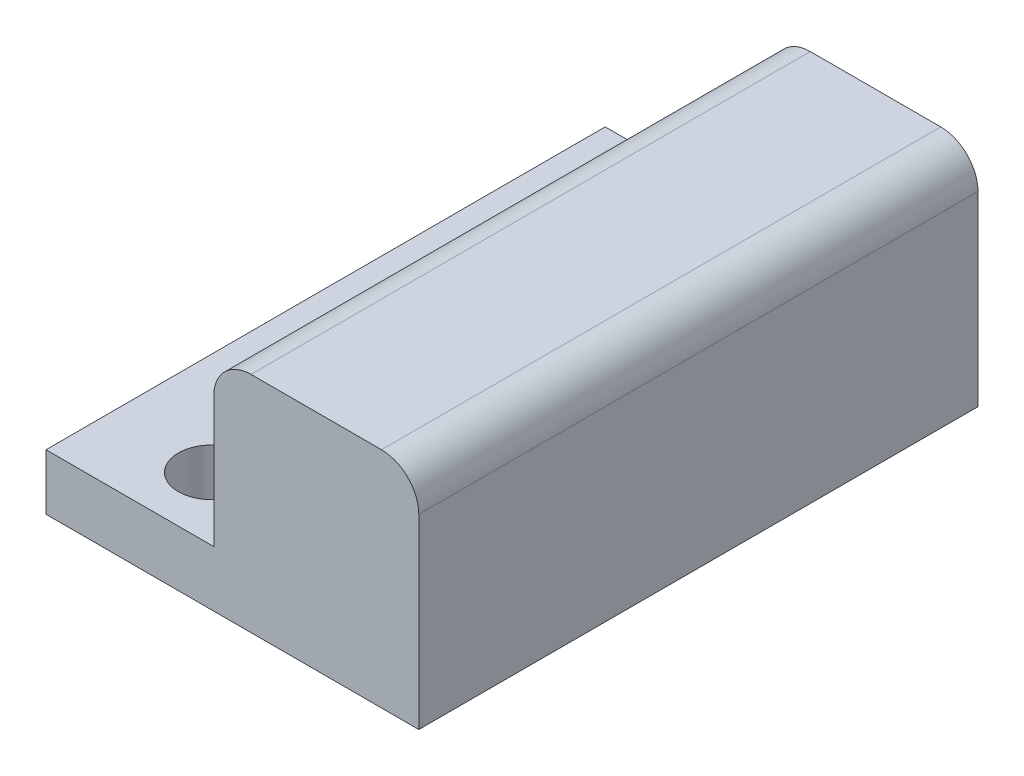
SolidWorks part; units mm, degrees
ref_plane "Front Plane" through (0, 0, 0) normal (0, 0, 1) x (1, 0, 0)
ref_plane "Top Plane" through (0, 0, 0) normal (0, 1, 0) x (1, 0, 0)
ref_plane "Right Plane" through (0, 0, 0) normal (1, 0, 0) x (0, 0, -1)
sketch "Sketch1" plane through (0, 0, 0) normal (0, 1, 0) x (1, 0, 0)
  line L1 (-19.9785, 6.6269) -> (5.4215, 6.6269)
  line L2 (-19.9785, 6.6269) -> (-19.9785, -31.4731)
  line L3 (-19.9785, -31.4731) -> (5.4215, -31.4731)
  line L4 (5.4215, 6.6269) -> (5.4215, -31.4731)
  circle A0 centre (1.6115, 1.4199) radius 2.286
  circle A1 centre (-1.5635, -27.1551) radius 2.286
  point P2 (-1.5635, -27.1551)
  point P6 (-19.9785, -12.4231)
  point P12 (0.3415, -12.4231)
  dimension "D1" = 28.575
  dimension "D2" = 4.572
  dimension "D3" = 3.81
  dimension "D4" = 3.175
  dimension "D5" = 38.1
  dimension "D6" = 25.4
  dimension "D7" = 4.318
extrude "Boss-Extrude1" add sketch "Sketch1" along normal blind 3.81
sketch "Sketch2" plane through (0, 3.81, 0) normal (0, 1, 0) x (1, 0, 0)
  line L0 (-19.9785, 6.6269) -> (-19.9785, -31.4731)
  line L1 (-19.9785, -31.4731) -> (-6.0085, -31.4731)
  line L2 (-19.9785, -31.4731) -> (5.4215, -31.4731) construction
  line L3 (-6.0085, -31.4731) -> (-6.0085, 6.6269)
  line L4 (5.4215, 6.6269) -> (-19.9785, 6.6269) construction
  line L5 (-6.0085, 6.6269) -> (-8.5485, 6.6269)
  line L6 (-8.5485, 6.6269) -> (-8.5485, -28.9331)
  line L7 (-8.5485, -28.9331) -> (-17.4385, -28.9331)
  line L8 (-17.4385, -28.9331) -> (-17.4385, 6.6269)
  line L9 (-17.4385, 6.6269) -> (-19.9785, 6.6269)
  dimension "D1" = 2.54
  dimension "D2" = 8.89
  dimension "D3" = 2.54
extrude "Boss-Extrude2" add sketch "Sketch2" along normal blind 8.89 contours L0 L1 L3 L5 L6 L7 L8 L9
sketch "Sketch3" plane through (0, 12.7, 0) normal (0, 1, 0) x (1, 0, 0)
  line L1 (-19.9785, 6.6269) -> (-6.0085, 6.6269)
  line L2 (-19.9785, 6.6269) -> (-19.9785, -31.4731)
  line L3 (-19.9785, -31.4731) -> (-6.0085, -31.4731)
  line L4 (-6.0085, 6.6269) -> (-6.0085, -31.4731)
extrude "Boss-Extrude3" add sketch "Sketch3" along normal blind 2.54
chamfer "Chamfer1" distance 1.27 angle 45 2 edges at (-8.5485, 12.7, 11.1531) (-17.4385, 12.7, 11.1531)
fillet "Fillet2" radius 2.54 2 edges at (-6.0085, 15.24, 12.4231) (-19.9785, 15.24, 12.4231)
mirror "Mirror1" about plane through (5.4215, 3.81, -6.6269) normal (-1, 0, 0) of bodies 103
delete or keep bodies "Body-Delete/Keep 1" type delete bodies bodies 103
